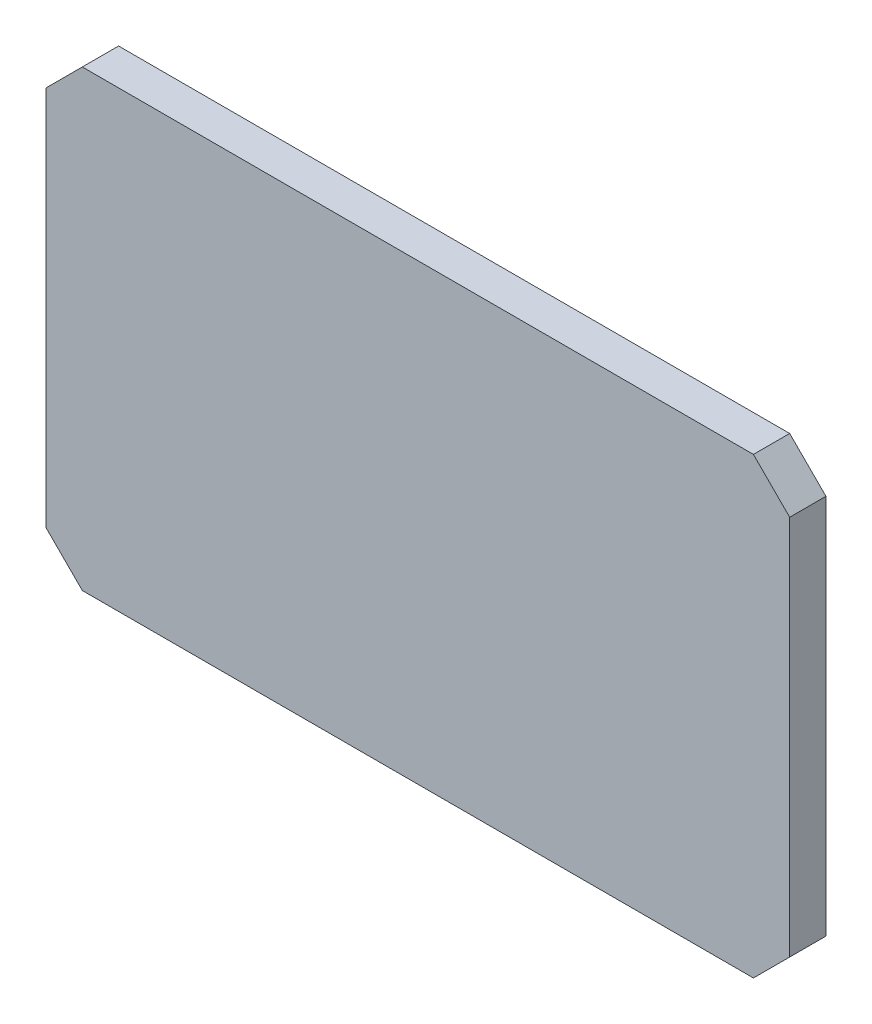
SolidWorks part; units mm, degrees
ref_plane "Front Plane" through (0, 0, 0) normal (0, 0, 1) x (1, 0, 0)
ref_plane "Top Plane" through (0, 0, 0) normal (0, 1, 0) x (1, 0, 0)
ref_plane "Right Plane" through (0, 0, 0) normal (1, 0, 0) x (0, 0, -1)
sketch "Sketch1" plane through (0, 0, 0) normal (0, 0, 1) x (1, 0, 0)
  line L0 (146.6256, 159.7193) -> (183.6256, 159.7193)
  line L1 (185.6256, 157.7193) -> (185.6256, 136.7193)
  line L2 (183.6256, 134.7193) -> (146.6256, 134.7193)
  line L3 (144.6256, 136.7193) -> (144.6256, 157.7193)
  line L6 (183.9856, 149.7194) -> (183.9856, 144.7194)
  line L8 (183.6256, 159.7193) -> (185.6256, 157.7193)
  line L9 (183.6256, 134.7193) -> (185.6256, 136.7193)
  line L10 (180.9856, 148.2194) -> (172.8363, 148.2194)
  line L11 (180.9856, 146.2194) -> (172.8421, 146.2194)
  line L12 (146.6256, 159.7193) -> (144.6256, 157.7193)
  line L13 (146.6256, 134.7193) -> (144.6256, 136.7193)
  line L15 (161.52, 152.2318) -> (156.8734, 147.9798)
  line L16 (161.5043, 142.2215) -> (156.8366, 146.487)
  line L17 (168.4511, 152.2318) -> (172.8363, 148.2194)
  line L18 (168.4669, 142.2215) -> (172.8421, 146.2194)
  line L19 (180.9856, 149.7194) -> (180.9856, 148.2194)
  line L20 (180.9856, 146.2194) -> (180.9856, 144.7194)
  arc A0 (183.9856, 149.7194) -> (180.9856, 149.7194) centre (182.4856, 149.7194) ccw
  arc A1 (180.9856, 144.7194) -> (183.9856, 144.7194) centre (182.4856, 144.7194) ccw
  arc A2 (168.4511, 152.2318) -> (161.52, 152.2318) centre (164.9856, 148.9388) ccw
  arc A3 (161.5043, 142.2215) -> (168.4669, 142.2215) centre (164.9856, 145.4979) ccw
  arc A5 (156.8734, 147.9798) -> (156.8366, 146.487) centre (157.4251, 147.2194) ccw
  point P8 (0, 0)
  point P9 (0, 0)
  point P16 (0, 0)
  point P17 (0, 0)
  point P22 (0, 0)
  point P23 (0, 0)
  point P30 (168.4511, 142.2215)
sketch "Sketch3" plane through (0, 0, 0) normal (0, 0, 1) x (1, 0, 0)
  line L0 (146.6256, 159.7193) -> (183.6256, 159.7193)
  line L1 (185.6256, 157.7193) -> (185.6256, 136.7193)
  line L2 (183.6256, 134.7193) -> (146.6256, 134.7193)
  line L3 (144.6256, 136.7193) -> (144.6256, 157.7193)
  line L4 (183.6256, 159.7193) -> (185.6256, 157.7193)
  line L5 (183.6256, 134.7193) -> (185.6256, 136.7193)
  line L6 (146.6256, 159.7193) -> (144.6256, 157.7193)
  line L7 (146.6256, 134.7193) -> (144.6256, 136.7193)
extrude "Boss-Extrude1" add sketch "Sketch3" along normal blind 2
sketch "Sketch4" plane through (0, 0, 0) normal (0, 0, 1) x (1, 0, 0)
  line L0 (183.9856, 149.7194) -> (183.9856, 144.7194)
  line L1 (180.9856, 148.2194) -> (172.8363, 148.2194)
  line L2 (180.9856, 146.2194) -> (172.8421, 146.2194)
  line L3 (161.52, 152.2318) -> (156.8734, 147.9798)
  line L4 (161.5043, 142.2215) -> (156.8366, 146.487)
  line L5 (168.4511, 152.2318) -> (172.8363, 148.2194)
  line L6 (168.4669, 142.2215) -> (172.8421, 146.2194)
  line L7 (180.9856, 149.7194) -> (180.9856, 148.2194)
  line L8 (180.9856, 146.2194) -> (180.9856, 144.7194)
  arc A0 (183.9856, 149.7194) -> (180.9856, 149.7194) centre (182.4856, 149.7194) ccw
  arc A1 (180.9856, 144.7194) -> (183.9856, 144.7194) centre (182.4856, 144.7194) ccw
  arc A2 (168.4511, 152.2318) -> (161.52, 152.2318) centre (164.9856, 148.9388) ccw
  arc A3 (161.5043, 142.2215) -> (168.4669, 142.2215) centre (164.9856, 145.4979) ccw
  arc A4 (156.8734, 147.9798) -> (156.8366, 146.487) centre (157.4251, 147.2194) ccw
extrude "Cut-Extrude2" cut sketch "Sketch4" along normal blind 1
